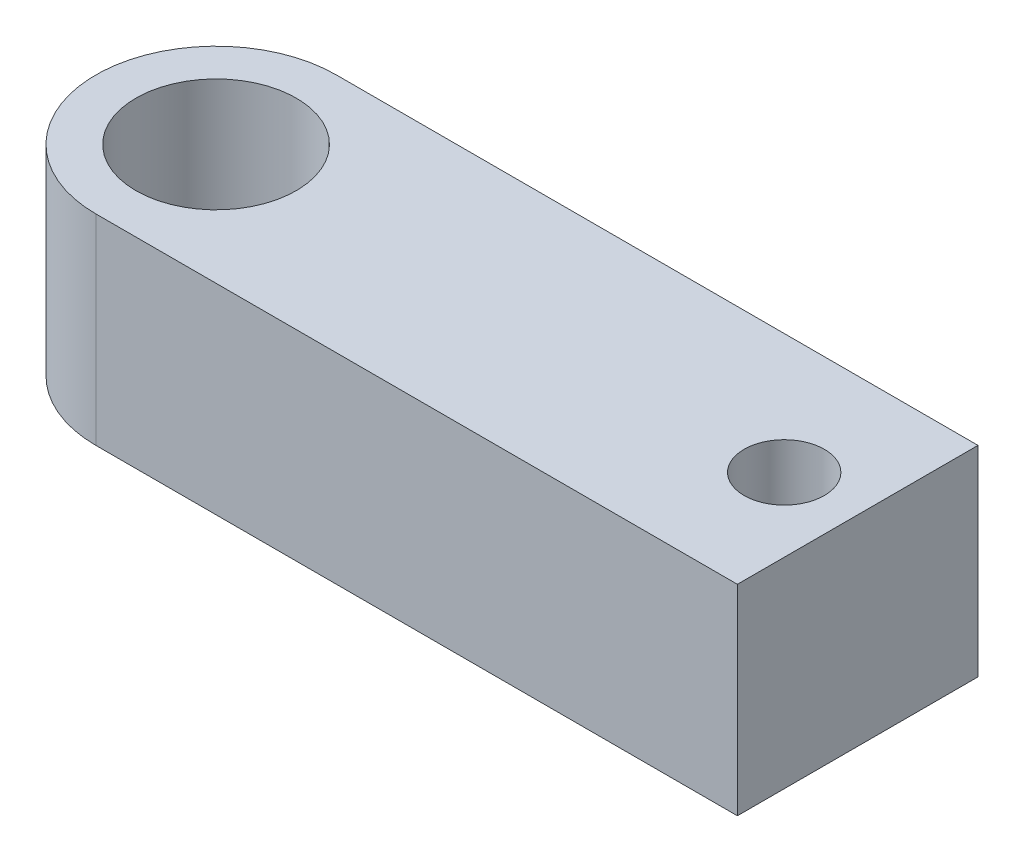
SolidWorks part; units mm, degrees
ref_plane "前视基准面" through (0, 0, 0) normal (0, 0, 1) x (1, 0, 0)
ref_plane "上视基准面" through (0, 0, 0) normal (0, 1, 0) x (1, 0, 0)
ref_plane "右视基准面" through (0, 0, 0) normal (1, 0, 0) x (0, 0, -1)
sketch "草图2" plane through (0, 0, 0) normal (0, 1, 0) x (1, 0, 0)
  line L0 (0, 3) -> (16, 3)
  line L1 (16, 3) -> (16, -3)
  line L2 (16, 0) -> (0, 0) construction
  line L3 (0, -3) -> (16, -3)
  arc A0 (0, 3) -> (0, -3) centre (0, 0) ccw
  dimension "D1" = 6
  dimension "D2" = 6
  dimension "D3" = 16
extrude "凸台-拉伸1" add sketch "草图2" along normal blind 5
sketch "草图3" plane through (0, 5, 0) normal (0, 1, 0) x (1, 0, 0)
  circle A0 centre (0, 0) radius 2
  dimension "D1" = 4
extrude "切除-拉伸1" cut sketch "草图3" against normal blind 5
sketch "草图4" plane through (0, 5, 0) normal (0, 1, 0) x (1, 0, 0)
  circle A0 centre (14.1676, 0) radius 1
  dimension "D1" = 2
extrude "切除-拉伸2" cut sketch "草图4" against normal blind 5
